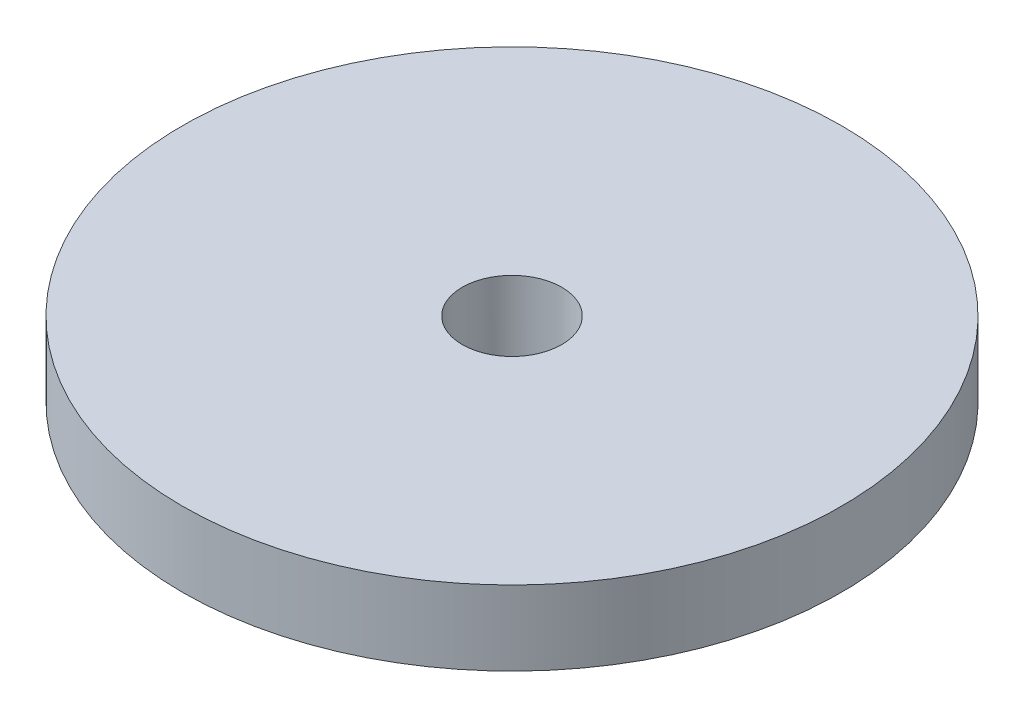
SolidWorks part; units mm, degrees
ref_plane "Front Plane" through (0, 0, 0) normal (0, 0, 1) x (1, 0, 0)
ref_plane "Top Plane" through (0, 0, 0) normal (0, 1, 0) x (1, 0, 0)
ref_plane "Right Plane" through (0, 0, 0) normal (1, 0, 0) x (0, 0, -1)
sketch "Sketch1" plane through (0, 0, 0) normal (0, 0, 1) x (1, 0, 0)
  line L0 (0, 0) -> (0, 6)
  line L1 (0, 6) -> (-22.5, 6)
  line L2 (-22.5, 6) -> (-22.5, 11)
  line L3 (-22.5, 11) -> (-26.5, 11)
  line L4 (0, 0) -> (-13, 0)
  line L5 (-13, 0) -> (-13, -3)
  line L6 (-26.5, 11) -> (-26.5, -3) construction
  line L7 (-26.5, -3) -> (-13, -3)
  line L8 (-26.5, -3) -> (-26.5, 11)
  dimension "D1" = 22.5
  dimension "D2" = 13
  dimension "D3" = 3
  dimension "D4" = 6
  dimension "D5" = 5
  dimension "D6" = 4
revolve "Revolve1" add sketch "Sketch1" angle 360 about L6
sketch "Sketch4" plane through (0, 0, 0) normal (0, 1, 0) x (1, 0, 0)
  line L0 (0, 0) -> (-53, 0)
  circle A0 centre (-26.5, 0) radius 26.5 construction
  circle A1 centre (-26.5, 0) radius 4
extrude "Cut-Extrude1" cut sketch "Sketch4" against normal through all and the other way through all contours A1
